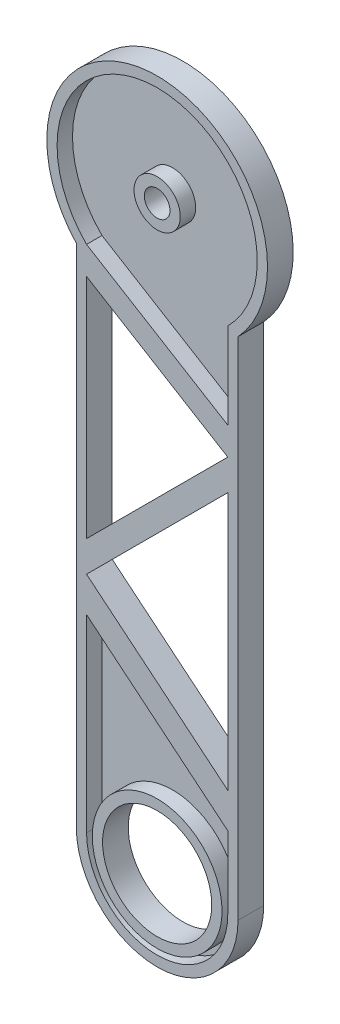
SolidWorks part; units mm, degrees
ref_plane "Front Plane" through (0, 0, 0) normal (0, 0, 1) x (1, 0, 0)
ref_plane "Top Plane" through (0, 0, 0) normal (0, 1, 0) x (1, 0, 0)
ref_plane "Right Plane" through (0, 0, 0) normal (1, 0, 0) x (0, 0, -1)
sketch "Sketch1" plane through (0, 0, 0) normal (0, 0, 1) x (1, 0, 0)
  line L0 (-11.3944, 89.7486) -> (-11.3944, -35.2514)
  line L1 (28.6056, 89.7486) -> (28.6056, -35.2514)
  circle A2 centre (8.6056, -35.2514) radius 13.5
  arc A3 (-11.3944, -35.2514) -> (28.6056, -35.2514) centre (8.6056, -35.2514) ccw
  circle A5 centre (8.6056, 108.3157) radius 3.175
  arc A6 (-11.3944, 89.7486) -> (28.6056, 89.7486) centre (8.6056, 108.3157) cw
  dimension "D3" = 27
  dimension "D5" = 6.35
  dimension "D1" = 40
  dimension "D4" = 125
extrude "Boss-Extrude1" add sketch "Sketch1" along normal blind 6.35
shell "Shell1" thickness 2.54
sketch "Sketch2" plane through (0, 0, 6.35) normal (0, 0, 1) x (1, 0, 0)
  line L0 (-8.8544, 27.7614) -> (26.0656, 62.6814)
  line L1 (-8.8544, 90.7742) -> (-8.8544, -35.2514) construction
  line L2 (26.0656, -35.2514) -> (26.0656, 90.7742) construction
  line L3 (26.0656, 62.6814) -> (26.0656, 55.0614)
  line L4 (26.0656, -35.2514) -> (26.0656, 90.7742) construction
  line L5 (26.0656, 55.0614) -> (-8.8544, 20.1414)
  line L6 (-8.8544, 20.1414) -> (-8.8544, 27.7614)
  line L7 (-8.8544, 20.1414) -> (26.0656, 20.1414) construction
  line L8 (-8.8544, 27.7614) -> (26.0656, 27.7614) construction
  dimension "D1" = 45
  dimension "D2" = 7.62
extrude "Boss-Extrude2" add sketch "Sketch2" against normal up to surface (3.81 mm away) up to face at (-7.4344, -35.2514, 2.54)
sketch "Sketch3" plane through (0, 0, 2.54) normal (0, 0, 1) x (1, 0, 0)
  line L0 (26.0656, 62.6814) -> (-8.8544, 83.9133)
  line L1 (-8.8544, 90.7742) -> (-8.8544, 27.7614) construction
  line L2 (-8.8544, 83.9133) -> (-8.8544, 90.7742)
  line L3 (-8.8544, 90.7742) -> (26.0656, 69.5422)
  line L4 (26.0656, 62.6814) -> (26.0656, 90.7742) construction
  line L5 (26.0656, 69.5422) -> (26.0656, 62.6814)
  line L6 (-8.8544, 20.1414) -> (26.0656, -8.6858)
  line L7 (26.0656, -35.2514) -> (26.0656, 55.0614) construction
  line L8 (26.0656, -8.6858) -> (26.0656, -17.3369)
  line L9 (26.0656, -35.2514) -> (26.0656, 55.0614) construction
  line L10 (26.0656, -17.3369) -> (-8.8544, 11.4903)
  line L11 (-8.8544, 20.1414) -> (-8.8544, -35.2514) construction
  line L12 (-8.8544, 11.4903) -> (-8.8544, 20.1414)
extrude "Boss-Extrude3" add sketch "Sketch3" along normal up to surface (3.81 mm away) up to face at (22.1056, -35.2514, 6.35)
sketch "Sketch4" plane through (0, 0, 2.54) normal (0, 0, 1) x (1, 0, 0)
  line L0 (-8.8544, 27.7614) -> (26.0656, 62.6814)
  line L1 (26.0656, 62.6814) -> (-8.8544, 83.9133)
  line L2 (-8.8544, 83.9133) -> (-8.8544, 27.7614)
  line L3 (-8.8544, 20.1414) -> (26.0656, -8.6858)
  line L4 (26.0656, -8.6858) -> (26.0656, 55.0614)
  line L5 (26.0656, 55.0614) -> (-8.8544, 20.1414)
extrude "Cut-Extrude1" cut sketch "Sketch4" against normal through all
